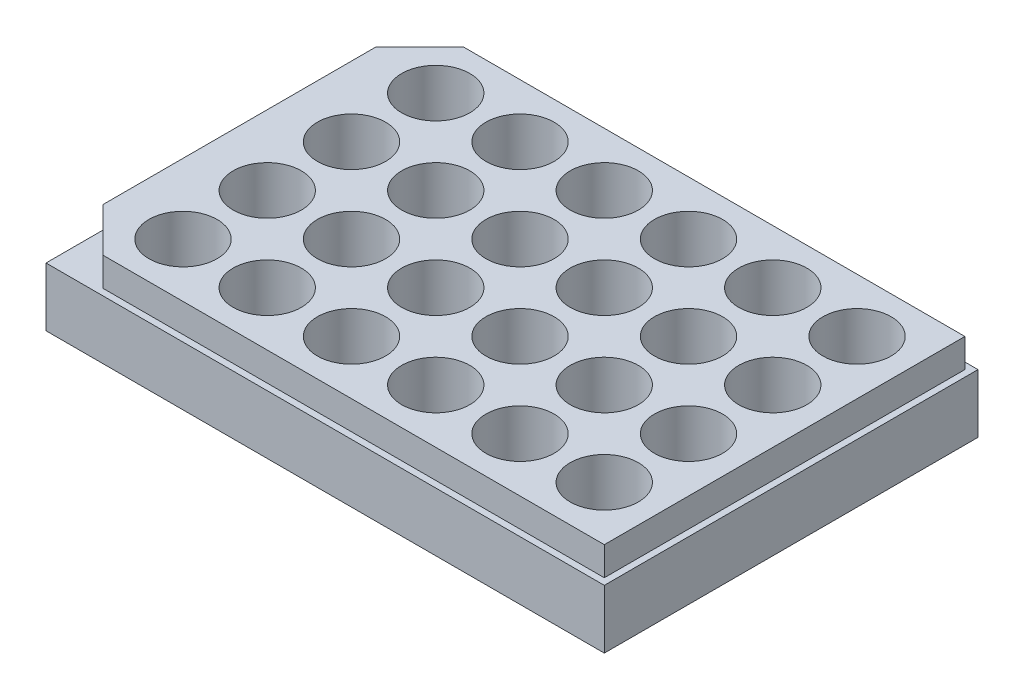
SolidWorks part; units mm, degrees
material "PVC Rigid"
ref_plane "Front Plane" through (0, 0, 0) normal (0, 0, 1) x (1, 0, 0)
ref_plane "Top Plane" through (0, 0, 0) normal (0, 1, 0) x (1, 0, 0)
ref_plane "Right Plane" through (0, 0, 0) normal (1, 0, 0) x (0, 0, -1)
sketch "Sketch1" plane through (0, 0, 0) normal (0, 1, 0) x (1, 0, 0)
  line L1 (-63.945, 42.8) -> (63.945, 42.8)
  line L2 (-63.945, 42.8) -> (-63.945, -42.8)
  line L3 (-63.945, -42.8) -> (63.945, -42.8)
  line L4 (63.945, 42.8) -> (63.945, -42.8)
  line L5 (-63.945, 42.8) -> (63.945, -42.8) construction
  line L6 (-63.945, -42.8) -> (63.945, 42.8) construction
  point P0 (0, 0)
  dimension "D1" = 127.89
  dimension "D2" = 85.6
extrude "Main Plate" add sketch "Sketch1" along normal blind 20.02
sketch "Wells_LSP" plane through (0, 20.02, 0) normal (0, 1, 0) x (1, 0, 0)
  line L0 (-46.425, 28.96) -> (-27.125, 28.96) construction
  line L4 (63.945, 42.8) -> (-63.945, 42.8) construction
  line L5 (-63.945, 42.8) -> (-63.945, -42.8) construction
  circle A0 centre (-46.425, 28.96) radius 7.81
  circle A1 centre (-27.125, 28.96) radius 7.81
  circle A2 centre (-7.825, 28.96) radius 7.81
  circle A3 centre (11.475, 28.96) radius 7.81
  circle A4 centre (30.775, 28.96) radius 7.81
  circle A5 centre (50.075, 28.96) radius 7.81
  circle A6 centre (-27.125, 9.66) radius 7.81
  circle A7 centre (-7.825, 9.66) radius 7.81
  circle A8 centre (11.475, 9.66) radius 7.81
  circle A9 centre (30.775, 9.66) radius 7.81
  circle A10 centre (50.075, 9.66) radius 7.81
  circle A11 centre (-27.125, -9.64) radius 7.81
  circle A12 centre (-7.825, -9.64) radius 7.81
  circle A13 centre (11.475, -9.64) radius 7.81
  circle A14 centre (30.775, -9.64) radius 7.81
  circle A15 centre (50.075, -9.64) radius 7.81
  circle A16 centre (-27.125, -28.94) radius 7.81
  circle A17 centre (-7.825, -28.94) radius 7.81
  circle A18 centre (11.475, -28.94) radius 7.81
  circle A19 centre (30.775, -28.94) radius 7.81
  circle A20 centre (50.075, -28.94) radius 7.81
  circle A21 centre (-46.425, 9.66) radius 7.81
  circle A22 centre (-46.425, -9.64) radius 7.81
  circle A23 centre (-46.425, -28.94) radius 7.81
  dimension "D2" = 6
  dimension "D4" = 4
  dimension "D7" = 15.62
  dimension "D16" = 17.52
  dimension "D3" = 19.3
  dimension "D15" = 13.84
extrude "Wells Depth" cut sketch "Wells_LSP" against normal through all
sketch "Sketch7" plane through (0, 20.02, 0) normal (0, 1, 0) x (1, 0, 0)
  line L0 (62.445, 41.3) -> (-62.445, 41.3)
  line L1 (63.945, 42.8) -> (-63.945, 42.8)
  line L2 (63.945, 42.8) -> (63.945, -42.8)
  line L3 (63.945, -42.8) -> (-63.945, -42.8)
  line L4 (-63.945, 42.8) -> (-63.945, -42.8)
  line L5 (-62.445, 41.3) -> (-62.445, -41.3)
  line L6 (62.445, -41.3) -> (-62.445, -41.3)
  line L7 (62.445, 41.3) -> (62.445, -41.3)
  point P0 (0, 0)
  dimension "D1" = 1.5
extrude "Flange" cut sketch "Sketch7" against normal blind 6.57
sketch "Style Sketch" plane through (0, 20.02, 0) normal (0, 1, 0) x (1, 0, 0)
  line L0 (-62.445, 41.3) -> (-52.445, 41.3)
  line L1 (62.445, 41.3) -> (-62.445, 41.3) construction
  line L2 (-52.445, 41.3) -> (-62.445, 31.3)
  line L3 (-62.445, 41.3) -> (-62.445, -41.3) construction
  line L4 (-62.445, 31.3) -> (-62.445, 41.3)
  line L5 (-62.445, -41.3) -> (-52.445, -41.3)
  line L6 (-62.445, -41.3) -> (62.445, -41.3) construction
  line L7 (-62.445, -41.3) -> (-62.445, -31.3)
  line L8 (-62.445, -31.3) -> (-52.445, -41.3)
  dimension "D1" = 10
  dimension "D2" = 10
  dimension "D3" = 10
  dimension "D4" = 10
extrude "Style <3" cut sketch "Style Sketch" against normal blind 6.57
ref_point "A1"
ref_point "A2"
ref_point "B1"
ref_plane "A1A2" through (0, 0, -28.96) normal (0, 0, -1) x (-1, 0, 0)
ref_plane "A1B1" through (-46.425, 0, 0) normal (1, 0, 0) x (0, 0, -1)
ref_plane "Plane3" through (0, 0, 0) normal (-1, 0, 0) x (0, 0, 1)
ref_point "D6"
ref_point "D5"
ref_point "C6"
ref_plane "D5D6" through (0, 0, 28.94) normal (0, 0, 1) x (1, 0, 0)
ref_plane "C6D6" through (50.075, 0, 0) normal (1, 0, 0) x (0, 0, -1)
equation "\"D1\"= 0.32"
equation "\"D1\"= 1.27 - 0.32"
